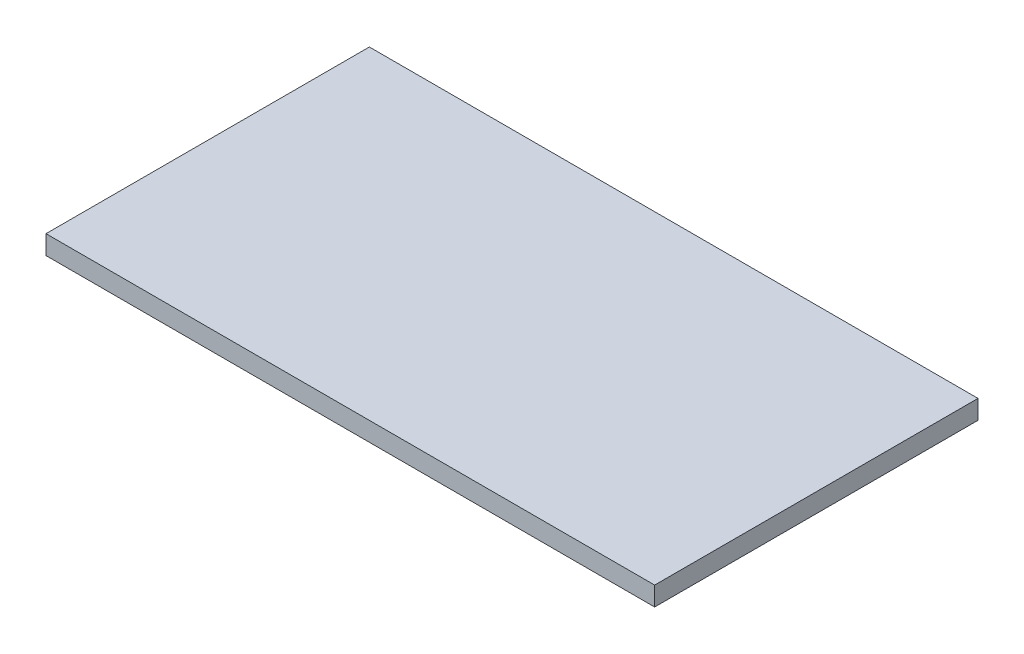
SolidWorks part; units mm, degrees
material "Kiefer"
ref_plane "Ebene vorne" through (0, 0, 0) normal (0, 0, 1) x (1, 0, 0)
ref_plane "Ebene oben" through (0, 0, 0) normal (0, 1, 0) x (1, 0, 0)
ref_plane "Ebene rechts" through (0, 0, 0) normal (1, 0, 0) x (0, 0, -1)
sketch "Skizze1" plane through (0, 0, 0) normal (0, 1, 0) x (1, 0, 0)
  line L1 (-160, 85) -> (160, 85)
  line L2 (-160, 85) -> (-160, -85)
  line L3 (-160, -85) -> (160, -85)
  line L4 (160, 85) -> (160, -85)
  line L5 (-160, 85) -> (160, -85) construction
  line L6 (-160, -85) -> (160, 85) construction
  point P0 (0, 0)
  dimension "D1" = 170
  dimension "D2" = 320
extrude "Aufsatz-Linear austragen1" add sketch "Skizze1" along normal blind 10
